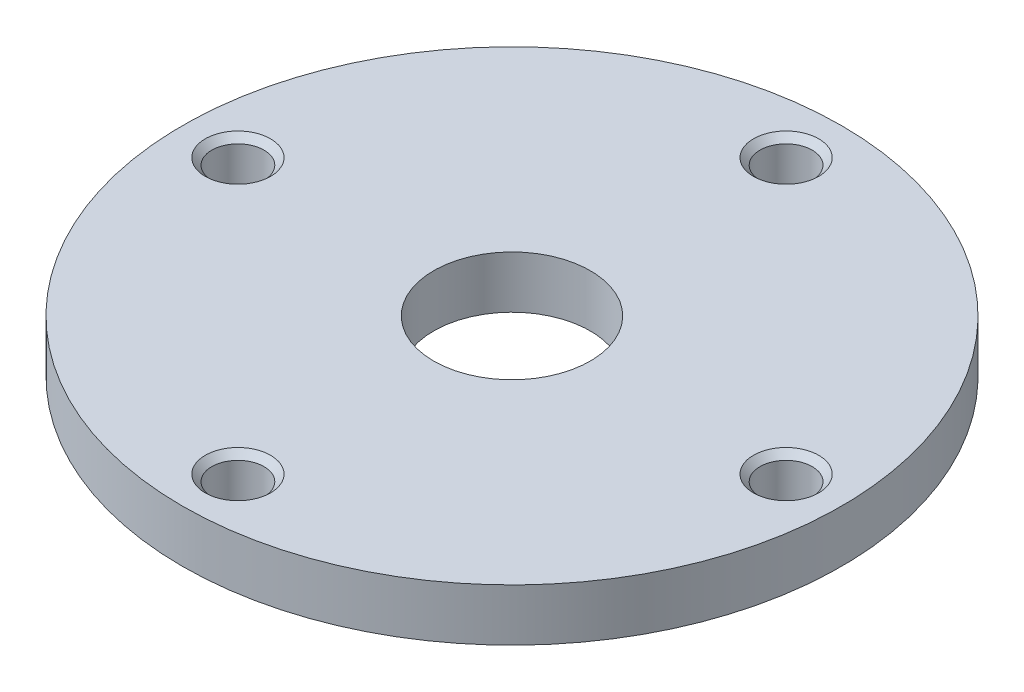
SolidWorks part; units mm, degrees
ref_plane "Front Plane" through (0, 0, 0) normal (0, 0, 1) x (1, 0, 0)
ref_plane "Top Plane" through (0, 0, 0) normal (0, 1, 0) x (1, 0, 0)
ref_plane "Right Plane" through (0, 0, 0) normal (1, 0, 0) x (0, 0, -1)
sketch "Sketch1" plane through (0, 0, 0) normal (0, 1, 0) x (1, 0, 0)
  circle A0 centre (0, 0) radius 12.625
  dimension "D1" = 25.25
extrude "Boss-Extrude1" add sketch "Sketch1" along normal blind 2
sketch "Sketch2" plane through (0, 2, 0) normal (0, 1, 0) x (1, 0, 0)
  line L0 (0, 0) -> (0, 10.5) construction
  circle A0 centre (0, 10.5) radius 0.5
  circle A1 centre (10.5, 0) radius 0.5
  circle A2 centre (0, -10.5) radius 0.5
  circle A3 centre (-10.5, 0) radius 0.5
  circle A4 centre (0, 0) radius 12.625 construction
  dimension "D1" = 1
  dimension "D2" = 10.5
  dimension "D3" = 4
extrude "Cut-Extrude1" cut sketch "Sketch2" against normal through all
hole_wizard "Ø2.0mm Dowel Hole1" positions "3DSketch1" profile "Sketch3" hole size "Ø2.0" standard "ANSI Metric" end condition through all
sketch3d "3DSketch1"
  line L0 (-10.5, 0, 0) -> (-10.5, 2, 0) construction
  line L1 (0, 0, -10.5) -> (0, 2, -10.5) construction
  line L2 (10.5, 0, 0) -> (10.5, 2, 0) construction
  line L3 (0, 0, 10.5) -> (0, 2, 10.5) construction
  point P0 (-10.5, 2, 0)
  point P4 (0, 2, -10.5)
  point P8 (10.5, 2, 0)
  point P12 (0, 2, 10.5)
sketch "Sketch3" plane through (-10.5, 2, 0) normal (1, 0, 0) x (0, 0, 1)
  line L0 (0, 0) -> (0, 2)
  line L1 (0, 2) -> (1, 2)
  line L2 (1, 2) -> (1, 0)
  line L5 (1, 0) -> (0, 0)
  line L11 (0, -6.35) -> (0, 107.95) construction
  dimension "Thru Hole Dia." = 2
  dimension "Thru Hole Depth" = 2
chamfer "Chamfer1" distance 0.25 angle 45 4 edges at (0, 2, 11.5) (-10.5, 2, 1) (10.5, 2, 1) (0, 2, -9.5)
sketch "Sketch4" plane through (0, 2, 0) normal (0, 1, 0) x (1, 0, 0)
  circle A0 centre (0, 0) radius 3
  dimension "D1" = 6
extrude "Cut-Extrude2" cut sketch "Sketch4" against normal blind 10
